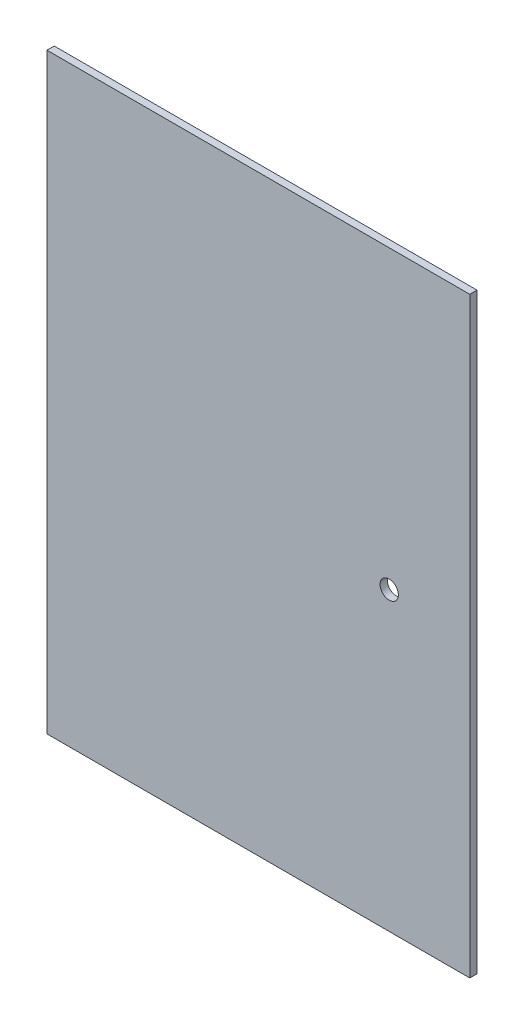
SolidWorks part; units mm, degrees
ref_plane "Front Plane" through (0, 0, 0) normal (0, 0, 1) x (1, 0, 0)
ref_plane "Top Plane" through (0, 0, 0) normal (0, 1, 0) x (1, 0, 0)
ref_plane "Right Plane" through (0, 0, 0) normal (1, 0, 0) x (0, 0, -1)
ref_plane "Plane1" through (0, 0, 8) normal (0, 0, 1) x (1, 0, 0)
sketch "Sketch1" plane through (0, 0, 8) normal (0, 0, 1) x (1, 0, 0)
  line L0 (-233.5, -327) -> (233.5, -327)
  line L1 (233.5, -327) -> (233.5, 327)
  line L2 (233.5, 327) -> (-233.5, 327)
  line L3 (-233.5, 327) -> (-233.5, -327)
  line L4 (0, 327) -> (0, 0) construction
  line L5 (0, 0) -> (144.5, 0) construction
  line L6 (144.5, 0) -> (233.5, 0) construction
  line L7 (131.5, -20) -> (171.5, -20) construction
  line L8 (131.5, -20) -> (131.5, 20) construction
  line L9 (171.5, -20) -> (171.5, 20) construction
  line L10 (131.5, 20) -> (171.5, 20) construction
  line L11 (131.5, -20) -> (171.5, 20) construction
  line L12 (171.5, -20) -> (131.5, 20) construction
  circle A0 centre (144.5, 0) radius 10.1
  point P11 (151.5, 0)
  dimension "D3" = 20.2
  dimension "D1" = 467
  dimension "D2" = 654
  dimension "D4" = 27
  dimension "D5" = 62
  dimension "D6" = 40
  dimension "D7" = 40
extrude "Boss-Extrude1" add sketch "Sketch1" against normal blind 8
